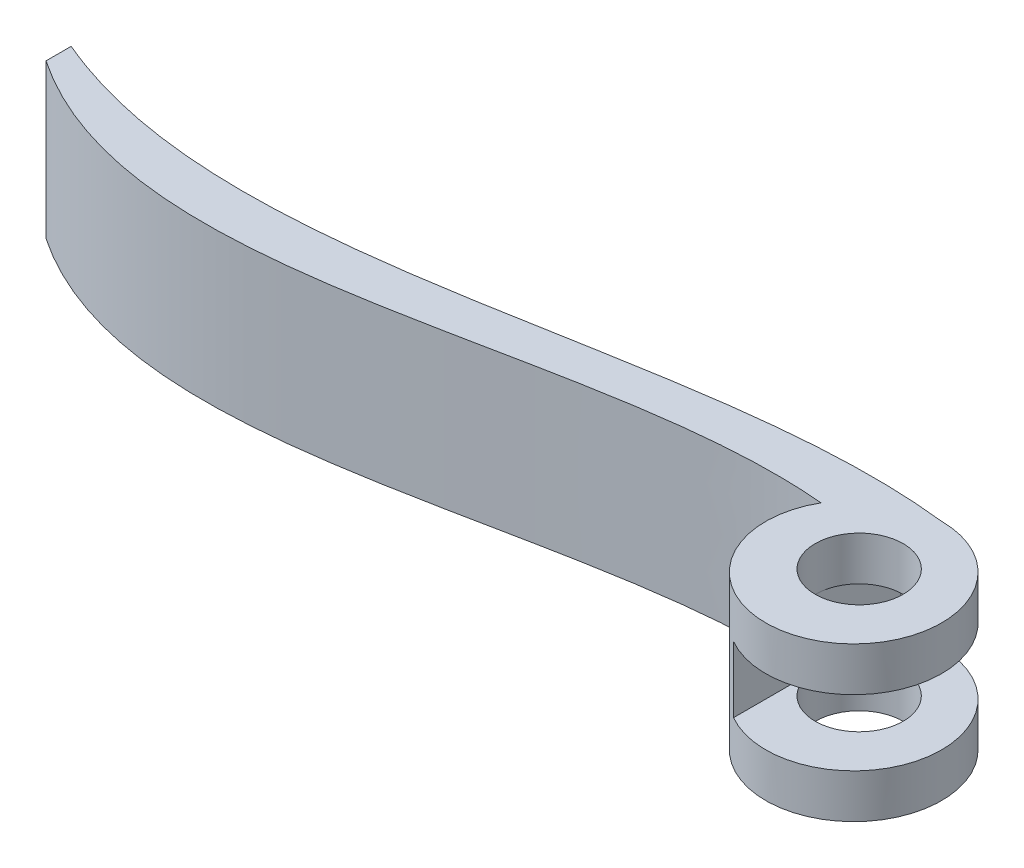
SolidWorks part; units mm, degrees
material "1023 Carbon Steel Sheet (SS)"
ref_plane "Front Plane" through (0, 0, 0) normal (0, 0, 1) x (1, 0, 0)
ref_plane "Top Plane" through (0, 0, 0) normal (0, 1, 0) x (1, 0, 0)
ref_plane "Right Plane" through (0, 0, 0) normal (1, 0, 0) x (0, 0, -1)
sketch "Sketch1" plane through (0, 0, 0) normal (0, 1, 0) x (1, 0, 0)
  line L0 (-77, 5.8325) -> (-77, 3.5409)
  arc A0 (-6.9423, 3.9755) -> (0, 8) centre (0, 0) ccw
  circle A1 centre (0, 0.5) radius 4
  spline S0 degree 3 poles (0, 8) (-24.8675, 10.8927) (-52.766, -4.51) (-77, 5.8325) knots 0 0 0 0 1 1 1 1
  spline S1 degree 3 poles (-6.9423, 3.9755) (-13.0889, 4.537) (-37.0642, 1.7219) (-62.0047, -6.5665) (-77, 3.5409) knots 0.045717 0.045717 0.045717 0.045717 0.300422 1 1 1 1
  dimension "D1" = 8
  dimension "D4" = 25.956
  dimension "D5" = 32.4192
  dimension "D6" = 69.9858
  dimension "D12" = 5.8325
  dimension "D2" = 8
  dimension "D3" = 6.9423
  dimension "D7" = 77
  dimension "D8" = 0.5
  dimension "D9" = 2.6444
  dimension "D10" = 3.5409
  dimension "D11" = 5.2296
extrude "Boss-Extrude1" add sketch "Sketch1" along normal blind 14
sketch "Sketch2" plane through (0, 0, 0) normal (0, 0, 1) x (1, 0, 0)
  line L0 (-4, 14) -> (-4, 0) construction
  line L1 (-4, 10) -> (8, 10)
  line L2 (-4, 10) -> (-4, 4)
  line L3 (-4, 4) -> (8, 4)
  line L4 (8, 10) -> (8, 4)
  line L5 (8, 0) -> (8, 14) construction
  line L6 (8, 14) -> (-8, 14) construction
  dimension "D1" = 4
  dimension "D2" = 6
extrude "Cut-Extrude1" cut sketch "Sketch2" along normal mid plane 34
